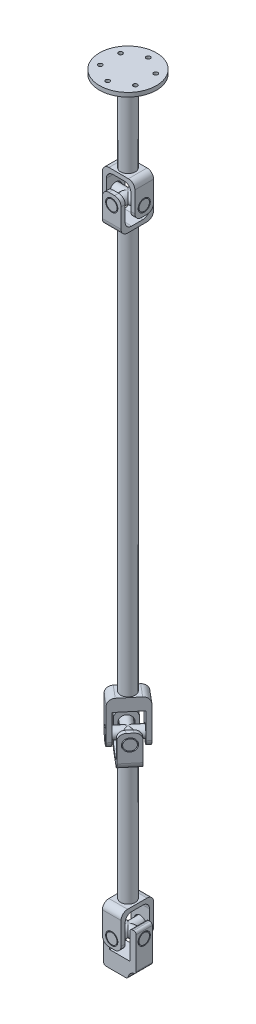
SolidWorks part; units mm, degrees
other "SC_E2"
other "UniJoint_1"
other "SC_E1"
other "UniJoint_3"
other "UniJoint_2"
other "SC_E4"
other "SC_E3"
ref_plane "Front Plane" through (0, 0, 0) normal (0, 0, 1) x (1, 0, 0)
ref_plane "Top Plane" through (0, 0, 0) normal (0, 1, 0) x (1, 0, 0)
ref_plane "Right Plane" through (0, 0, 0) normal (1, 0, 0) x (0, 0, -1)
sketch "Sketch2" plane through (0, 0, 0) normal (0, 1, 0) x (1, 0, 0)
  line L1 (20, -10) -> (-20, -10)
  line L2 (20, -10) -> (20, 10)
  line L3 (20, 10) -> (-20, 10)
  line L4 (-20, -10) -> (-20, 10)
  line L5 (20, -10) -> (-20, 10) construction
  line L6 (20, 10) -> (-20, -10) construction
  point P0 (0, 0)
  dimension "D1" = 40
  dimension "D2" = 20
extrude "Boss-Extrude1" add sketch "Sketch2" along normal blind 55
sketch "Sketch3" plane through (20, 0, 0) normal (1, 0, 0) x (0, 0, -1)
  line L0 (0, 43) -> (0, 55) construction
  line L1 (-10, 55) -> (10, 55) construction
  circle A0 centre (0, 43) radius 7.5
  dimension "D1" = 15
  dimension "D2" = 12
extrude "Cut-Extrude1" cut sketch "Sketch3" against normal through all
sketch "Sketch4" plane through (0, 0, 10) normal (0, 0, 1) x (1, 0, 0)
  line L0 (-20, 55) -> (20, 55) construction
  line L1 (-12.5, 55) -> (12.5, 55)
  line L2 (-12.5, 55) -> (-12.5, 20)
  line L3 (-12.5, 20) -> (12.5, 20)
  line L4 (12.5, 55) -> (12.5, 20)
  line L5 (-12.5, 37.5) -> (-20, 37.5) construction
  line L6 (-20, 55) -> (-20, 0) construction
  line L7 (12.5, 37.5) -> (20, 37.5) construction
  line L8 (20, 55) -> (20, 0) construction
  line L9 (20, 0) -> (20, 10)
  line L10 (20, 0) -> (10, 0)
  arc A0 (20, 10) -> (10, 0) centre (20, 0) ccw
  dimension "D3" = 20
  dimension "D1" = 25
  dimension "D2" = 35
extrude "Cut-Extrude2" cut sketch "Sketch4" against normal through all
fillet "Fillet1" radius 3 7 edges at (20, 55, 0) (-20, 55, 0) (10, 0, 0) (20, 10, 0) (-20, 0, 0) (12.5, 55, 0) (-12.5, 55, 0)
sketch "Sketch23" plane through (0, 0, 0) normal (0, -1, 0) x (1, 0, 0)
  line L0 (-17, 0) -> (7.3509, 0) construction
  line L1 (-17, 10) -> (-17, -10) construction
  line L2 (7.3509, -10) -> (7.3509, 10) construction
  line L3 (-4.8246, 10) -> (-4.8246, -10) construction
  line L4 (-17, 10) -> (7.3509, 10) construction
  line L5 (7.3509, -10) -> (-17, -10) construction
  circle A0 centre (-4.8246, 0) radius 5
  dimension "D1" = 10
extrude "Cut-Extrude8" cut sketch "Sketch23" against normal blind 10
sketch "Sketch5" plane through (-20, 0, 0) normal (-1, 0, 0) x (0, 0, 1)
  circle A0 centre (0, 43) radius 7.5 construction
  circle A1 centre (0, 43) radius 7.5 construction
  circle A2 centre (0, 43) radius 6.5
  dimension "D1" = 1
extrude "Boss-Extrude2" add sketch "Sketch5" against normal blind 40 separate body
sketch "Sketch6" plane through (0, 0, 0) normal (0, 0, 1) x (1, 0, 0)
  line L1 (-20, 36.5) -> (20, 36.5) construction
  line L2 (20, 49.5) -> (-20, 49.5) construction
  line L3 (-20, 43) -> (20, 43) construction
  line L4 (-20, 49.5) -> (-20, 36.5) construction
  line L5 (20, 36.5) -> (20, 49.5) construction
  circle A0 centre (0, 43) radius 6.5
extrude "Boss-Extrude3" add sketch "Sketch6" along normal mid plane 40
sketch "Sketch7" plane through (0, 0, 0) normal (1, 0, 0) x (0, 0, -1)
  line L0 (0, 43) -> (-15, 43) construction
  line L1 (-20, 32.5) -> (-15, 32.5)
  line L2 (-20, 32.5) -> (-20, 76)
  line L4 (-15, 32.5) -> (-15, 71)
  line L5 (15, 32.5) -> (20, 32.5)
  line L6 (15, 32.5) -> (15, 71)
  line L8 (20, 32.5) -> (20, 76)
  line L9 (-15, 71) -> (15, 71)
  line L11 (-20, 76) -> (20, 76)
  line L13 (0, 43) -> (15, 43) construction
  dimension "D1" = 5
  dimension "D2" = 40
  dimension "D3" = 4
  dimension "D4" = 28
  dimension "D5" = 5
extrude "Boss-Extrude4" add sketch "Sketch7" along normal mid plane 23 separate body
sketch "Sketch12" plane through (0, 0, -20) normal (0, 0, -1) x (-1, 0, 0)
  circle A0 centre (0, 43) radius 7.5
  circle A1 centre (0, 43) radius 6.5
  circle A2 centre (0, 43) radius 6.5 construction
  dimension "D2" = 1
  dimension "D1" = 0
extrude "Cut-Extrude4" cut sketch "Sketch12" against normal through all
sketch "Sketch8" plane through (0, 76, 0) normal (0, 1, 0) x (1, 0, 0)
  line L0 (0, 20) -> (0, -20) construction
  line L1 (11.5, 20) -> (-11.5, 20) construction
  line L2 (11.5, -20) -> (-11.5, -20) construction
  line L3 (11.5, 0) -> (-11.5, 0) construction
  line L4 (11.5, 20) -> (11.5, -20) construction
  line L5 (-11.5, 20) -> (-11.5, -20) construction
  circle A0 centre (0, 0) radius 9
  dimension "D1" = 18
extrude "Boss-Extrude5" add sketch "Sketch8" along normal blind 150
sketch "Sketch9" plane through (0, 226, 0) normal (0, 1, 0) x (1, 0, 0)
  line L0 (15.3209, -12.8558) -> (-15.3209, 12.8558) construction
  line L1 (-7.9288, 21.6653) -> (-22.7129, 4.0462)
  line L2 (7.9288, -21.6653) -> (22.7129, -4.0462)
  line L3 (-7.9288, 21.6653) -> (22.7129, -4.0462)
  line L4 (-22.7129, 4.0462) -> (7.9288, -21.6653)
  line L5 (0, 0) -> (-7.5335, 0) construction
  point P3 (0, 0)
  point P8 (-15.3209, 12.8558)
  point P11 (15.3209, -12.8558)
  dimension "D1" = 23
  dimension "D2" = 40
  dimension "D3" = 40
extrude "Boss-Extrude6" add sketch "Sketch9" along normal blind 5
sketch "Sketch10" plane through (0, 231, 0) normal (0, 1, 0) x (1, 0, 0)
  line L0 (7.9288, -21.6653) -> (22.7129, -4.0462) construction
  line L1 (-7.9288, 21.6653) -> (-22.7129, 4.0462) construction
  line L2 (7.9288, -21.6653) -> (22.7129, -4.0462)
  line L3 (-7.9288, 21.6653) -> (-22.7129, 4.0462)
  line L4 (-4.0986, 18.4513) -> (-18.8827, 0.8323)
  line L5 (4.0986, -18.4513) -> (18.8827, -0.8323)
  line L6 (-22.7129, 4.0462) -> (-18.8827, 0.8323)
  line L7 (-7.9288, 21.6653) -> (-4.0986, 18.4513)
  line L8 (18.8827, -0.8323) -> (22.7129, -4.0462)
  line L9 (4.0986, -18.4513) -> (7.9288, -21.6653)
  dimension "D1" = 5
extrude "Boss-Extrude7" add sketch "Sketch10" along normal blind 35
sketch "Sketch11" plane through (15.3209, 0, 12.8558) normal (0.766, 0, 0.6428) x (0.6428, 0, -0.766)
  line L0 (0, 253.5) -> (0, 266) construction
  line L1 (-11.5, 266) -> (11.5, 266) construction
  circle A0 centre (0, 253.5) radius 7.5
  dimension "D1" = 15
  dimension "D2" = 12.5
extrude "Cut-Extrude3" cut sketch "Sketch11" against normal through all
fillet "Fillet2" radius 8 16 edges at (11.5, 32.5, -17.5) (11.5, 32.5, 17.5) (-11.5, 32.5, 17.5) (-11.5, 32.5, -17.5) (0, 76, -20) (0, 76, 20) (-15.3209, 226, -12.8558) (15.3209, 226, 12.8558) (-6.0137, 266, -20.0583) (20.7978, 266, 2.4393) (6.0137, 266, 20.0583) (-20.7978, 266, -2.4393) (0, 71, -15) (0, 71, 15) (11.4907, 231, 9.6418) (-11.4907, 231, -9.6418)
sketch "Sketch24" plane through (15.3209, 0, 12.8558) normal (0.766, 0, 0.6428) x (0.6428, 0, -0.766)
  circle A0 centre (0, 253.5) radius 7.5 construction
  circle A1 centre (0, 253.5) radius 7.5 construction
  circle A2 centre (0, 253.5) radius 6.5
  dimension "D1" = 1
extrude "Boss-Extrude15" add sketch "Sketch24" against normal blind 40 separate body
ref_plane "Plane3" through (0, 0, 0) normal (-0.6428, 0, 0.766) x (0.766, 0, 0.6428)
sketch "Sketch25" plane through (0, 0, 0) normal (-0.6428, 0, 0.766) x (0.766, 0, 0.6428)
  line L0 (-20, 253.5) -> (20, 253.5) construction
  line L1 (-20, 260) -> (-20, 247) construction
  line L2 (20, 247) -> (20, 260) construction
  line L3 (-20, 247) -> (20, 247) construction
  line L4 (20, 260) -> (-20, 260) construction
  circle A0 centre (0, 253.5) radius 6.5
extrude "Boss-Extrude16" add sketch "Sketch25" along normal mid plane 40
ref_plane "Plane1" through (0, 0, 0) normal (-0.766, 0, -0.6428) x (-0.6428, 0, 0.766)
sketch "Sketch13" plane through (0, 0, 0) normal (-0.766, 0, -0.6428) x (-0.6428, 0, 0.766)
  line L0 (-15, 242) -> (-15, 282)
  line L5 (0, 246) -> (0, 242) construction
  line L6 (-20, 242) -> (-15, 242)
  line L8 (-20, 242) -> (-20, 297)
  line L9 (-20, 297) -> (20, 297)
  line L10 (20, 242) -> (20, 297)
  line L11 (-15, 282) -> (15, 282)
  line L12 (15, 282) -> (15, 242)
  line L13 (15, 242) -> (20, 242)
  line L14 (0, 253.5) -> (-15, 253.5) construction
  line L15 (0, 253.5) -> (15, 253.5) construction
  circle A0 centre (0, 253.5) radius 7.5 construction
  circle A1 centre (0, 253.5) radius 7.5 construction
  dimension "D1" = 40
  dimension "D2" = 5
  dimension "D3" = 55
  dimension "D4" = 15
  dimension "D5" = 30
  dimension "D6" = 4
extrude "Boss-Extrude8" add sketch "Sketch13" along normal mid plane 20 separate body
sketch "Sketch14" plane through (0, 297, 0) normal (0, 1, 0) x (1, 0, 0)
  circle A0 centre (0, 0) radius 9
  dimension "D1" = 18
extrude "Boss-Extrude9" add sketch "Sketch14" along normal blind 500
sketch "Sketch15" plane through (0, 797, 0) normal (0, 1, 0) x (1, 0, 0)
  line L1 (11.5, -20) -> (-11.5, -20)
  line L2 (11.5, -20) -> (11.5, 20)
  line L3 (11.5, 20) -> (-11.5, 20)
  line L4 (-11.5, -20) -> (-11.5, 20)
  line L5 (11.5, -20) -> (-11.5, 20) construction
  line L6 (11.5, 20) -> (-11.5, -20) construction
  point P0 (0, 0)
  dimension "D1" = 23
  dimension "D2" = 40
extrude "Boss-Extrude10" add sketch "Sketch15" along normal blind 5
sketch "Sketch16" plane through (0, 802, 0) normal (0, 1, 0) x (1, 0, 0)
  line L0 (11.5, -20) -> (11.5, 20) construction
  line L1 (-11.5, 20) -> (11.5, 20)
  line L2 (-11.5, 20) -> (-11.5, 15)
  line L3 (-11.5, 15) -> (11.5, 15)
  line L4 (11.5, 20) -> (11.5, 15)
  line L5 (-11.5, 20) -> (-11.5, -20) construction
  line L6 (11.5, -20) -> (-11.5, -20)
  line L7 (11.5, -20) -> (11.5, -15)
  line L8 (11.5, -15) -> (-11.5, -15)
  line L9 (-11.5, -20) -> (-11.5, -15)
  dimension "D1" = 5
extrude "Boss-Extrude11" add sketch "Sketch16" along normal blind 35
sketch "Sketch17" plane through (0, 0, 20) normal (0, 0, 1) x (1, 0, 0)
  line L0 (-11.5, 837) -> (11.5, 837) construction
  line L1 (0, 837) -> (0, 825) construction
  circle A0 centre (0, 825) radius 7.5
  dimension "D1" = 12
  dimension "D2" = 15
extrude "Cut-Extrude5" cut sketch "Sketch17" against normal through all
fillet "Fillet3" radius 8 14 edges at (-12.8558, 297, 15.3209) (-18.9092, 242, 6.9779) (-3.5883, 242, 19.8337) (18.9092, 242, -6.9779) (3.5883, 242, -19.8337) (12.8558, 297, -15.3209) (11.5, 837, -17.5) (11.5, 837, 17.5) (-11.5, 837, 17.5) (-11.5, 837, -17.5) (0, 802, -15) (0, 797, -20) (0, 802, 15) (0, 797, 20)
sketch "Sketch21" plane through (-12.8558, 0, 15.3209) normal (-0.6428, 0, 0.766) x (0.766, 0, 0.6428)
  line L0 (0, 246) -> (0, 242) construction
  line L1 (-2, 242) -> (2, 242) construction
  circle A0 centre (0, 253.5) radius 7.5
  dimension "D2" = 15
  dimension "D1" = 4
extrude "Cut-Extrude6" cut sketch "Sketch21" against normal through all
sketch "Sketch26" plane through (0, 0, 20) normal (0, 0, 1) x (1, 0, 0)
  circle A0 centre (0, 825) radius 7.5 construction
  circle A1 centre (0, 825) radius 7.5 construction
  circle A2 centre (0, 825) radius 6.5
  dimension "D1" = 1
extrude "Boss-Extrude17" add sketch "Sketch26" against normal blind 40 separate body
ref_plane "Plane4" through (0, 0, 0) normal (-1, 0, 0) x (0, 0, 1)
sketch "Sketch27" plane through (0, 0, 0) normal (-1, 0, 0) x (0, 0, 1)
  line L0 (-20, 825) -> (20, 825) construction
  line L1 (-20, 831.5) -> (-20, 818.5) construction
  line L2 (20, 818.5) -> (20, 831.5) construction
  line L3 (20, 831.5) -> (-20, 831.5) construction
  circle A0 centre (0, 825) radius 6.5
extrude "Boss-Extrude18" add sketch "Sketch27" along normal mid plane 40
ref_plane "Plane2" through (0, 0, 0) normal (0, 0, -1) x (-1, 0, 0)
sketch "Sketch18" plane through (0, 0, 0) normal (0, 0, -1) x (-1, 0, 0)
  line L0 (-15, 813.5) -> (-15, 850)
  line L1 (-20, 813.5) -> (-15, 813.5)
  line L2 (-20, 813.5) -> (-20, 855)
  line L3 (-20, 855) -> (20, 855)
  line L4 (20, 813.5) -> (20, 855)
  line L5 (-15, 850) -> (15, 850)
  line L6 (15, 850) -> (15, 813.5)
  line L7 (15, 813.5) -> (20, 813.5)
  line L8 (0, 825) -> (-15, 825) construction
  line L9 (0, 825) -> (15, 825) construction
  line L10 (0, 817.5) -> (0, 813.5) construction
  circle A0 centre (0, 825) radius 7.5 construction
  circle A1 centre (0, 825) radius 7.5 construction
  dimension "D1" = 40
  dimension "D2" = 4
  dimension "D3" = 5
  dimension "D4" = 5
  dimension "D5" = 25
extrude "Boss-Extrude12" add sketch "Sketch18" along normal mid plane 23 separate body
sketch "Sketch19" plane through (0, 855, 0) normal (0, 1, 0) x (1, 0, 0)
  circle A0 centre (0, 0) radius 9
  dimension "D1" = 18
extrude "Boss-Extrude13" add sketch "Sketch19" along normal blind 100
fillet "Fillet4" radius 8 8 edges at (20, 855, 0) (15, 850, 0) (-15, 850, 0) (17.5, 813.5, 11.5) (17.5, 813.5, -11.5) (-17.5, 813.5, 11.5) (-17.5, 813.5, -11.5) (-20, 855, 0)
sketch "Sketch20" plane through (0, 955, 0) normal (0, 1, 0) x (1, 0, 0)
  line L0 (0, 0) -> (0, 35) construction
  circle A0 centre (0, 0) radius 35
  circle A1 centre (0, 25) radius 2.5
  circle A2 centre (21.6506, 12.5) radius 2.5
  circle A3 centre (21.6506, -12.5) radius 2.5
  circle A4 centre (0, -25) radius 2.5
  circle A5 centre (-21.6506, -12.5) radius 2.5
  circle A6 centre (-21.6506, 12.5) radius 2.5
  point P18 (0, 0)
  dimension "D1" = 70
  dimension "D2" = 5
  dimension "D3" = 25
  dimension "D4" = 6
extrude "Boss-Extrude14" add sketch "Sketch20" along normal blind 5
sketch "Sketch22" plane through (-20, 0, 0) normal (-1, 0, 0) x (0, 0, 1)
  line L0 (0, 817.5) -> (0, 813.5) construction
  line L1 (-3.5, 813.5) -> (3.5, 813.5) construction
  circle A0 centre (0, 825) radius 7.5
  dimension "D2" = 15
  dimension "D1" = 4
extrude "Cut-Extrude7" cut sketch "Sketch22" against normal through all
other "Save Bodies1"
